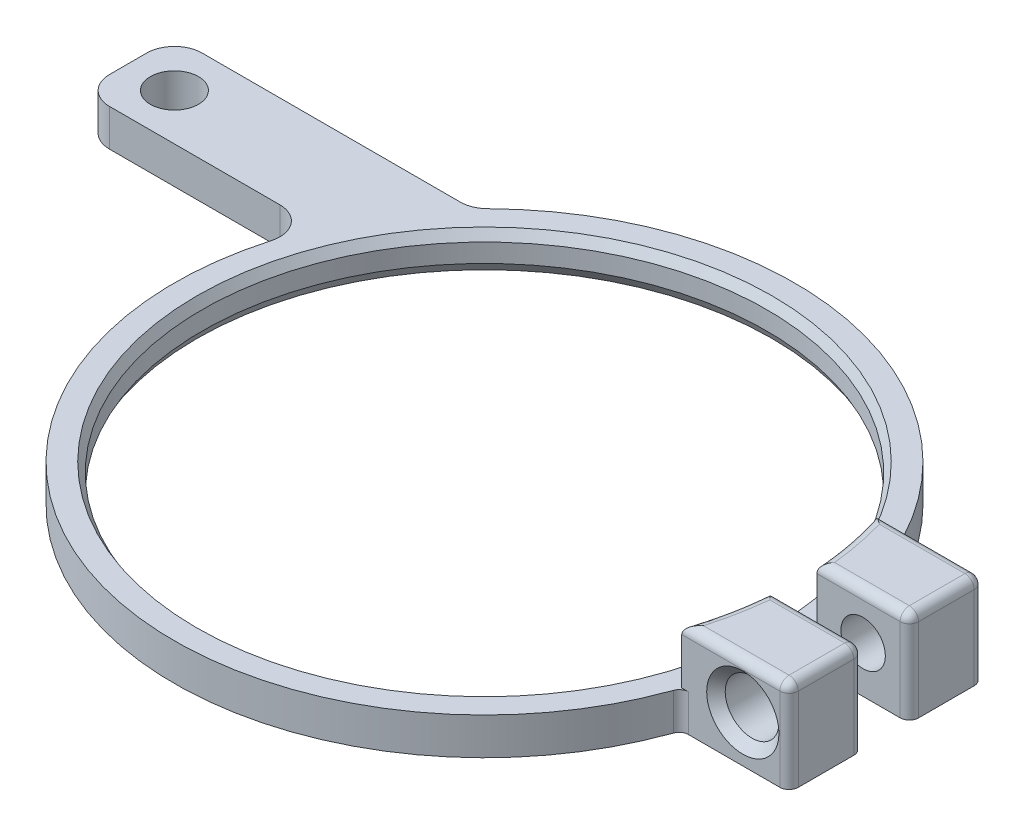
SolidWorks part; units mm, degrees
ref_plane "前基準面" through (0, 0, 0) normal (0, 0, 1) x (1, 0, 0)
ref_plane "上基準面" through (0, 0, 0) normal (0, 1, 0) x (1, 0, 0)
ref_plane "右基準面" through (0, 0, 0) normal (1, 0, 0) x (0, 0, -1)
sketch "草圖1" plane through (0, 0, 0) normal (0, 1, 0) x (1, 0, 0)
  circle A0 centre (0, 0) radius 30.5
  circle A2 centre (0, 0) radius 33.5
  dimension "D1" = 61
  dimension "D2" = 3
extrude "填料-伸長1" add sketch "草圖1" along normal mid plane 4
sketch "草圖3" plane through (0, 2, 0) normal (0, 1, 0) x (1, 0, 0)
  line L0 (0, 0) -> (35.3974, 0) construction
  line L1 (40.3974, -2.5) -> (30.3974, -2.5)
  line L2 (40.3974, -2.5) -> (40.3974, 2.5)
  line L3 (40.3974, 2.5) -> (30.3974, 2.5)
  line L4 (30.3974, -2.5) -> (30.3974, 2.5)
  line L5 (40.3974, -2.5) -> (30.3974, 2.5) construction
  line L6 (40.3974, 2.5) -> (30.3974, -2.5) construction
  circle A0 centre (0, 0) radius 30.5 construction
  point P0 (35.3974, 0)
  dimension "D1" = 5
  dimension "D2" = 10
extrude "除料-伸長1" cut sketch "草圖3" against normal through all
sketch "草圖4" plane through (0, -2, 0) normal (0, 1, 0) x (1, 0, 0)
  line L0 (33.4066, -2.5) -> (43.4066, -2.5)
  line L1 (43.4066, -2.5) -> (43.4066, -10.5)
  line L2 (43.4066, -10.5) -> (31.8119, -10.5)
  line L3 (0, 0) -> (12.6628, 0) construction
  line L4 (43.4066, 10.5) -> (31.8119, 10.5)
  line L5 (43.4066, 2.5) -> (43.4066, 10.5)
  line L6 (33.4066, 2.5) -> (43.4066, 2.5)
  arc A0 (33.4066, 2.5) -> (33.4066, -2.5) centre (0, 0) ccw construction
  arc A1 (33.4066, 2.5) -> (31.8119, 10.5) centre (0, 0) ccw
  arc A2 (31.8119, -10.5) -> (33.4066, -2.5) centre (0, 0) ccw
  dimension "D1" = 8
  dimension "D2" = 10
extrude "填料-伸長2" add sketch "草圖4" along normal blind 10
sketch "草圖5" plane through (0, 0, 10.5) normal (0, 0, 1) x (1, 0, 0)
  line L0 (43.4066, 3) -> (38.4066, 3) construction
  line L1 (43.4066, -2) -> (43.4066, 8) construction
  circle A0 centre (38.4066, 3) radius 2.9
  dimension "D1" = 5.8
  dimension "D2" = 5
extrude "除料-伸長2" cut sketch "草圖5" against normal offset from surface (6 mm away) 2 up to face at (35.7368, 2.6667, 2.5)
sketch "草圖6" plane through (0, 0, 4.5) normal (0, 0, 1) x (1, 0, 0)
  circle A0 centre (38.4066, 3) radius 2.4
  dimension "D1" = 4.8
extrude "除料-伸長3" cut sketch "草圖6" against normal through all
fillet "圓角9" radius 1 2 edges at (31.8119, 0, -10.5) (31.8119, 0, 10.5)
fillet "圓角11" radius 1 4 edges at (43.4066, 3, -10.5) (43.4066, 3, -2.5) (43.4066, 3, 2.5) (43.4066, 3, 10.5)
fillet "圓角12" radius 1 12 edges at (37.1093, 8, -10.5) (43.1137, 8, -10.2071) (43.4066, 8, -6.5) (43.1137, 8, -2.7929) (37.9066, 8, 2.5) (43.1137, 8, 2.7929) (43.4066, 8, 6.5) (43.1137, 8, 10.2071) (37.9066, 8, -2.5) (37.1093, 8, 10.5) (32.8537, 8, -6.5487) (32.8537, 8, 6.5487)
chamfer "導角1" distance 1 angle 45 1 edges at (41.3066, 3, 10.5)
sketch "草圖7" plane through (0, 2, 0) normal (0, 1, 0) x (1, 0, 0)
  line L5 (-30.8747, 13) -> (-56.5, 13)
  line L7 (-24.3567, 23) -> (-56.5, 23)
  line L8 (-56.5, 13) -> (-56.5, 23)
  line L9 (-30.0653, 14.776) -> (-56.5, 23) construction
  line L10 (-24.3567, 23) -> (-56.5, 13) construction
  arc A0 (-24.3567, 23) -> (-30.8747, 13) centre (0, 0) ccw
  circle A2 centre (-51.5, 18) radius 2.6
  arc A3 (31.5841, 11.1667) -> (31.5841, -11.1667) centre (0, 0) ccw construction
  point P5 (-40.4284, 18)
  dimension "D3" = 5.2
  dimension "D1" = 18
  dimension "D2" = 18
  dimension "D4" = 5
  dimension "D5" = 5
  dimension "D6" = 5
extrude "填料-伸長3" add sketch "草圖7" against normal up to surface (4 mm away) up to face at (29.0646, -2, 0)
fillet "圓角13" radius 3 4 edges at (-56.5, 0, -13) (-56.5, 0, -23) (-30.8747, 0, -13) (-24.3567, 0, -23)
chamfer "導角2" distance 1 angle 30 1 edges at (-30.5, 2, 0)
chamfer "導角3" distance 1 angle 30 1 edges at (-30.5, -2, 0)
fillet "圓角14" radius 1 2 edges at (30.3974, 0, -2.5) (30.3974, 0, 2.5)
